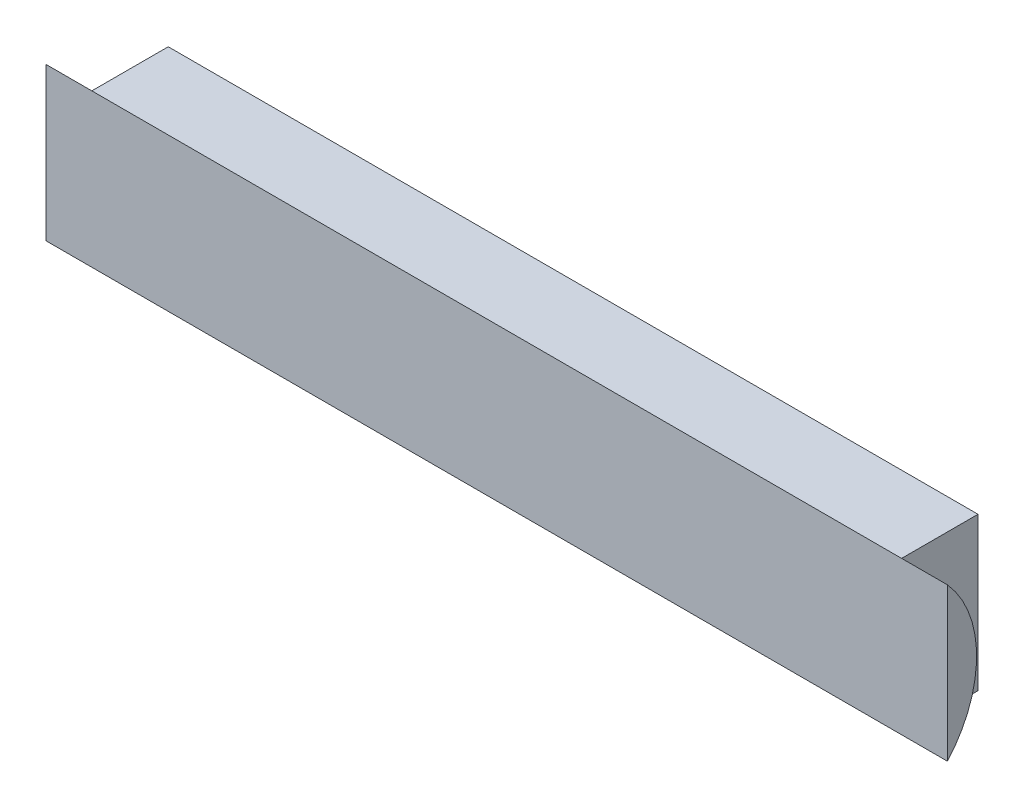
SolidWorks part; units mm, degrees
ref_plane "前视基准面" through (0, 0, 0) normal (0, 0, 1) x (1, 0, 0)
ref_plane "上视基准面" through (0, 0, 0) normal (0, 1, 0) x (1, 0, 0)
ref_plane "右视基准面" through (0, 0, 0) normal (1, 0, 0) x (0, 0, -1)
sketch "草图1" plane through (0, 0, 0) normal (0, 0, 1) x (1, 0, 0)
  line L1 (-26.5, 5) -> (26.5, 5)
  line L2 (-26.5, 5) -> (-26.5, -5)
  line L3 (-26.5, -5) -> (26.5, -5)
  line L4 (26.5, 5) -> (26.5, -5)
  line L5 (-26.5, 5) -> (26.5, -5) construction
  line L6 (-26.5, -5) -> (26.5, 5) construction
  point P0 (0, 0)
  dimension "D1" = 53
  dimension "D2" = 10
extrude "凸台-拉伸1" add sketch "草图1" along normal blind 5
sketch "草图2" plane through (26.5, 0, 0) normal (1, 0, 0) x (0, 0, -1)
  line L0 (-5, -5) -> (-5, 5) construction
  line L2 (-5, 5) -> (-5, -5)
  arc A0 (-5, 5) -> (-5, -5) centre (-10.5902, 0) cw
  dimension "D1" = 7.5
extrude "凸台-拉伸2" add sketch "草图2" along normal blind 3
sketch "草图3" plane through (-26.5, 0, 0) normal (-1, 0, 0) x (0, 0, 1)
  line L0 (5, -5) -> (5, 5)
  arc A0 (5, -5) -> (5, 5) centre (10.5902, 0) cw
  dimension "D1" = 7.5
extrude "凸台-拉伸3" add sketch "草图3" along normal blind 3
